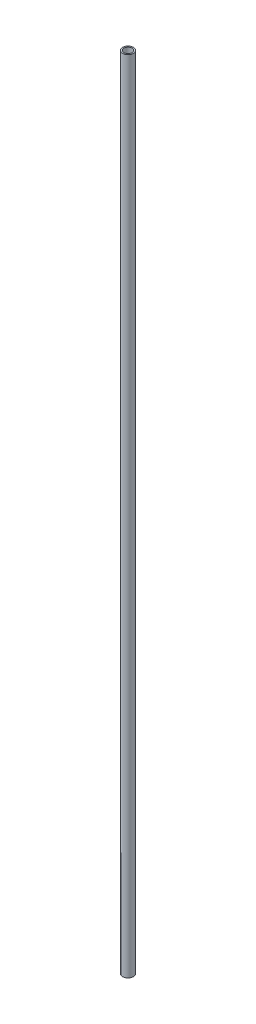
SolidWorks part; units mm, degrees
material "Hexcel AS4C (3000 Filaments)"
ref_plane "Front Plane" through (0, 0, 0) normal (0, 0, 1) x (1, 0, 0)
ref_plane "Top Plane" through (0, 0, 0) normal (0, 1, 0) x (1, 0, 0)
ref_plane "Right Plane" through (0, 0, 0) normal (1, 0, 0) x (0, 0, -1)
sketch "Sketch1" plane through (0, 0, 0) normal (0, 1, 0) x (1, 0, 0)
  circle A0 centre (0, 0) radius 4
  circle A1 centre (0, 0) radius 3
  dimension "D1" = 8
  dimension "D2" = 6
extrude "Boss-Extrude1" add sketch "Sketch1" against normal mid plane 600
